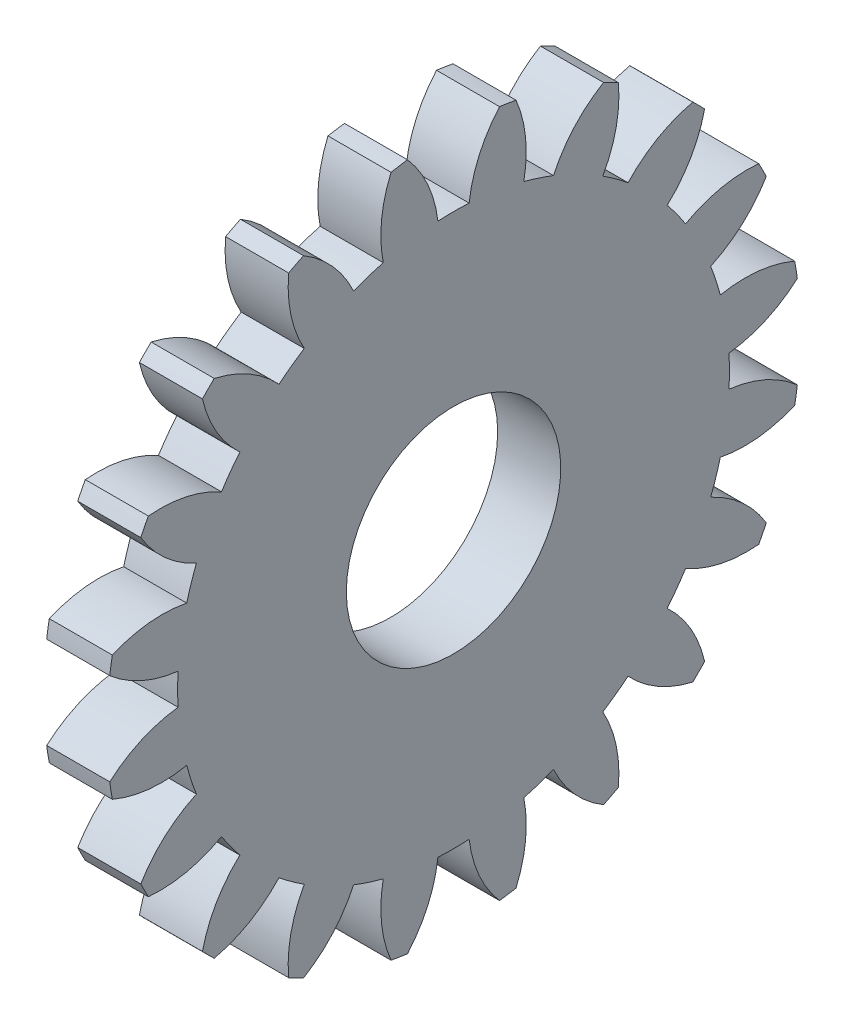
SolidWorks part; units mm, degrees
ref_plane "Plane1" through (0, 0, 0) normal (0, 0, 1) x (1, 0, 0)
ref_plane "Plane2" through (0, 0, 0) normal (0, 1, 0) x (1, 0, 0)
ref_plane "Plane3" through (0, 0, 0) normal (1, 0, 0) x (0, 0, -1)
sketch "HoldingSke" plane through (0, 0, 0) normal (0, 1, 0) x (1, 0, 0)
  line L0 (0, 0) -> (0.3759, -0.1368)
  line L1 (-15, 0) -> (100, 0) construction
  line L2 (0, 0) -> (-2.1039, 2.3779)
  line L3 (0, 0) -> (-11.863, 4.5341)
  line L4 (0, 0) -> (8.1152, 2.9537)
  line L5 (0, 0) -> (-46.8476, -17.4728)
  line L6 (0, 0) -> (-4.1448, -2.7965)
  line L7 (-2.1039, 2.3779) -> (8.6586, 51.2059)
  line L8 (-76.2, 54.61) -> (-73.4, 54.61)
  line L9 (-71.009, 38.7566) -> (-53.1078, 45.2721)
  line L10 (-76.2, 71.12) -> (104.1128, 71.12)
  line L11 (0, 0) -> (-5, 0)
  line L12 (-76.2, 101.6) -> (-76.113, 101.6)
  line L13 (24.9733, 27.94) -> (52.9518, 28.4284)
  line L14 (24.9733, 27.94) -> (24.9743, 27.94)
  line L15 (24.9733, 27.94) -> (100.4006, 29.5858)
  line L16 (-63.627, -2.5) -> (-12.827, -2.5)
  circle A0 centre (0, 0) radius 8.5
  circle A1 centre (0, 0) radius 21.874
  circle A2 centre (0, 0) radius 37.5
  circle A3 centre (0, 0) radius 8.5
  dimension "MHD" = 43.748
  dimension "Hub_dia" = 75
  dimension "Bore" = 17
  dimension "MBD" = 17
  dimension "Num_teeth" = 20
  dimension "Pitch" = 0.4
  dimension "Overall_len" = 50
  dimension "Show_teeth" = 20
  dimension "Thickness" = 5
  dimension "OAL" = 50.0001
  dimension "T_dim" = 2.8
  dimension "Ap" = 20
  dimension "H" = 19.05
  dimension "Pitch_radius" = 180.3128
  dimension "Width" = 5
  dimension "Backlash" = 0.087
  dimension "Addendum_fac" = 1
  dimension "Dedendum_fac" = 1.25
  dimension "Clearance_fac" = 0.25
  dimension "Dedendum_add" = 0.001
  dimension "Module" = 2.5
sketch "BasProSke" plane through (0, 0, 0) normal (0, 1, 0) x (1, 0, 0)
  line L0 (-10, 0) -> (60, 0) construction
  line L1 (0, 0) -> (0, 27.5)
  line L2 (0, 0) -> (5, 0)
  line L3 (5, 0) -> (5, 27.5)
  line L4 (5, 27.5) -> (0, 27.5)
  dimension "Thickness" = 5
  dimension "Diameter" = 55
revolve "Base-Revolve" add sketch "BasProSke" angle 360 about L0
sketch "TooCutSke" plane through (0, 0, 0) normal (1, 0, 0) x (0, 0, -1)
  line L1 (0, 0) -> (0, 107) construction
  line L2 (0, 0) -> (-2.1137, 24.9105) construction
  line L3 (0, 0) -> (-7.8012, 49.2549) construction
  line L4 (-2.1137, 24.9105) -> (-3.9006, 24.6275) construction
  arc A0 (1.2377, 21.839) -> (-1.2377, 21.839) centre (0, 0) ccw
  arc A1 (3.6672, 27.28) -> (-3.6672, 27.28) centre (0, 0) ccw
  circle A2 centre (0, 0) radius 25 construction
  circle A3 centre (0, 0) radius 23.4923 construction
  arc A4 (-1.2377, 21.839) -> (-3.6672, 27.28) centre (-11.1689, 20.6675) ccw
  arc A5 (3.6672, 27.28) -> (1.2377, 21.839) centre (11.1689, 20.6675) ccw
  dimension "Root_dia" = 43.748
  dimension "Overcut_dia" = 55.0508
  dimension "Pitch_dia" = 50
  dimension "Base_dia" = 46.9846
  dimension "Flank_rad" = 10
  dimension "Half_ang" = 9
  dimension "Half_CT" = 1.8092
extrude "ToothCut" cut sketch "TooCutSke" along normal through all
fillet "Breaks" [suppressed] radius 0.05
fillet "RootFillets" [suppressed] radius 0.626
pattern_circular "TeethCuts" count 20 every 18 about axis through (-10, 0, 0) along (1, 0, 0) of "ToothCut", "RootFillets", "Breaks"
sketch "HubNeaOneSke" plane through (0, 0, 0) normal (-1, 0, 0) x (0, 0, 1)
  circle A0 centre (0, 0) radius 21.874
  dimension "Diameter" = 43.748
extrude "HubNearOne" [suppressed] add sketch "HubNeaOneSke" along normal blind 45.0001
sketch "HubNeaBotSke" plane through (0, 0, 0) normal (-1, 0, 0) x (0, 0, 1)
  circle A0 centre (0, 0) radius 21.874
  dimension "Diameter" = 43.748
extrude "HubNearBoth" [suppressed] add sketch "HubNeaBotSke" along normal blind 22.5
ref_plane "FarPln" through (5, 0, 0) normal (1, 0, 0) x (0, 0, -1)
sketch "HubFarSke" plane through (5, 0, 0) normal (1, 0, 0) x (0, 0, -1)
  circle A0 centre (0, 0) radius 21.874
  dimension "Diameter" = 43.748
extrude "HubFar" [suppressed] add sketch "HubFarSke" along normal blind 22.5
sketch "BorSke" plane through (0, 0, 0) normal (1, 0, 0) x (0, 0, -1)
  circle A0 centre (0, 0) radius 8.5
  dimension "Diameter" = 17
extrude "Bore" cut sketch "BorSke" along normal mid plane 100.0001
sketch "KeySke" plane through (0, 0, 0) normal (1, 0, 0) x (0, 0, -1)
  line L0 (-3, 0) -> (-3, 11.3)
  line L1 (-3, 11.3) -> (3, 11.3)
  line L2 (3, 11.3) -> (3, 0)
  line L3 (0, 0) -> (0, 34) construction
  line L4 (-3, 0) -> (3, 0)
  dimension "Offset" = 11.3
  dimension "Width" = 6
extrude "Keyway" [suppressed] cut sketch "KeySke" along normal mid plane 100.0001
pattern_circular "Keyway2" [suppressed] count 2 every 90 about axis through (-10, 0, 0) along (1, 0, 0)
equation "' \"Module@HoldingSke\" = 6.35"
equation "' \"Num_teeth@HoldingSke\" = 12"
equation "' \"Ap@HoldingSke\" =  20"
equation "' \"Ap@HoldingSke\" = 20"
equation "' \"Width@HoldingSke\" = 0.5 * 25.4"
equation "' \"Hub_dia@HoldingSke\"= 1 * 25.4"
equation "' \"Hub_dia@HoldingSke\" = 1 * 25.4"
equation "' \"Overall_len@HoldingSke\" = 1.0 * 25.4"
equation "' \"Bore@HoldingSke\" = 0.75 * 25.4"
equation "' \"T_dim@HoldingSke\" = 0.1 * 25.4"
equation "' \"Width@KeySke\" = 0.25 * 25.4"
equation "' \"Show_teeth@HoldingSke\" = 13"
equation "' \"Backlash@HoldingSke\" = 0.009 * 25.4"
equation "' \"Addendum_fac@HoldingSke\" = 1.0"
equation "' \"Dedendum_fac@HoldingSke\" = 1.25"
equation "' \"Dedendum_add@HoldingSke\" = 0.00005 * 25.4"
equation "' \"Clearance_fac@HoldingSke\" = 0.25"
equation "\"Pitch@HoldingSke\" = 1 / \"Module@HoldingSke\""
equation "\"Overcut_dia@TooCutSke\" = (\"Num_teeth@HoldingSke\" + 2 * \"Addendum_fac@HoldingSke\") / \"Pitch@HoldingSke\" + 0.002 * 25.4"
equation "\"Pitch_dia@TooCutSke\" = \"Num_teeth@HoldingSke\" / \"Pitch@HoldingSke\""
equation "\"Base_dia@TooCutSke\" = \"Num_teeth@HoldingSke\" / \"Pitch@HoldingSke\" * cos((\"Ap@HoldingSke\"  * 3.14159265 / 180))"
equation "\"Root_dia@TooCutSke\" = (\"Num_teeth@HoldingSke\" + 2) / \"Pitch@HoldingSke\" - 2 * (\"Addendum_fac@HoldingSke\" + \"Dedendum_fac@HoldingSke\") / \"Pitch@HoldingSke\" - \"Dedendum_add@HoldingSke\" * 2"
equation "\"Half_ang@TooCutSke\" = 180 / \"Num_teeth@HoldingSke\""
equation "\"Half_CT@TooCutSke\" = \"Num_teeth@HoldingSke\" / \"Pitch@HoldingSke\" * sin((3.14159265 / 2 / \"Num_teeth@HoldingSke\")) / 2 - 7 * \"Backlash@HoldingSke\" / 4"
equation "\"Flank_rad@TooCutSke\" = \"Num_teeth@HoldingSke\" / \"Pitch@HoldingSke\" / 5"
equation "\"Radius@RootFillets\" = \"Clearance_fac@HoldingSke\" / \"Pitch@HoldingSke\" + \"Dedendum_add@HoldingSke\""
equation "\"Break_rad@Breaks\" = 0.02 / \"Pitch@HoldingSke\""
equation "\"Thickness@HoldingSke\" = \"Width@HoldingSke\""
equation "\"OAL@HoldingSke\" = \"Thickness@HoldingSke\""
equation "\"MHD@HoldingSke\" = (\"Num_teeth@HoldingSke\" + 2) / \"Pitch@HoldingSke\" - 2 * (\"Addendum_fac@HoldingSke\" + \"Dedendum_fac@HoldingSke\")  / \"Pitch@HoldingSke\" - \"Dedendum_add@HoldingSke\" * 2"
equation "\"MBD@HoldingSke\" = (\"Num_teeth@HoldingSke\" + 2) / \"Pitch@HoldingSke\" - 2 * (\"Addendum_fac@HoldingSke\" + \"Dedendum_fac@HoldingSke\")  / \"Pitch@HoldingSke\" - \"Dedendum_add@HoldingSke\" * 2 - 0.002 * 25.4"
equation "\"MHD@HoldingSke\" = ((sgn( \"MHD@HoldingSke\" - \"Hub_dia@HoldingSke\" )-1)*( \"MHD@HoldingSke\" - \"Hub_dia@HoldingSke\" ))/-2+ \"Hub_dia@HoldingSke\""
equation "\"MBD@HoldingSke\" = ((sgn( \"MBD@HoldingSke\" - \"Bore@HoldingSke\" )-1)*( \"MBD@HoldingSke\" - \"Bore@HoldingSke\" ))/-2+ \"Bore@HoldingSke\""
equation "\"OAL@HoldingSke\" = ((sgn( \"OAL@HoldingSke\" - \"Overall_len@HoldingSke\" )+1)*( \"OAL@HoldingSke\" - \"Overall_len@HoldingSke\" ))/2 + \"Overall_len@HoldingSke\" + 0.000002 * 25.4"
equation "\"Num_teeth@TeethCuts\" = int( \"Show_teeth@HoldingSke\" ) + 1"
equation "\"Num_teeth@TeethCuts\" = ((sgn( \"Num_teeth@TeethCuts\" - \"Num_teeth@HoldingSke\" )-1)*( \"Num_teeth@TeethCuts\" - \"Num_teeth@HoldingSke\" ))/-2+ \"Num_teeth@HoldingSke\""
equation "\"Num_teeth@TeethCuts\" = ((sgn( \"Num_teeth@TeethCuts\" - 2.0)+1)*( \"Num_teeth@TeethCuts\" - 2.0))/2 +2.0"
equation "\"Angle@TeethCuts\" = 360.0 / \"Num_teeth@HoldingSke\""
equation "\"Diameter@BasProSke\" = (\"Num_teeth@HoldingSke\" + 2 * \"Addendum_fac@HoldingSke\") / \"Pitch@HoldingSke\""
equation "\"Thickness@BasProSke\"  = \"Thickness@HoldingSke\""
equation "' \"Fillet_rad@BasProSke\" =  \"Thickness@HoldingSke\" * 0.05"
equation "' \"Fillet_rad@BasProSke\" = \"Thickness@HoldingSke\" * 0.05"
equation "\"MHD@HoldingSke\" = ((sgn( \"MHD@HoldingSke\" - \"Root_dia@TooCutSke\" )-1)*( \"MHD@HoldingSke\" - \"Root_dia@TooCutSke\" ))/-2+ \"Root_dia@TooCutSke\""
equation "\"Diameter@HubNeaOneSke\" = \"MHD@HoldingSke\""
equation "\"Length@HubNearOne\" = \"OAL@HoldingSke\" - \"Thickness@BasProSke\""
equation "\"Diameter@HubNeaBotSke\" = \"MHD@HoldingSke\""
equation "\"Length@HubNearBoth\" = ( \"OAL@HoldingSke\" - \"Thickness@BasProSke\" ) / 2.0"
equation "\"Thickness@FarPln\" = \"Thickness@BasProSke\""
equation "\"Diameter@HubFarSke\" = \"MHD@HoldingSke\""
equation "\"Length@HubFar\" = ( \"OAL@HoldingSke\" - \"Thickness@BasProSke\" ) / 2.0"
equation "\"Diameter@BorSke\" = \"MBD@HoldingSke\""
equation "\"D1@Bore\" = \"OAL@HoldingSke\" * 2.0"
equation "\"D1@Keyway\" = \"OAL@HoldingSke\" * 2.0"
equation "\"Offset@KeySke\" = \"T_dim@HoldingSke\" + \"MBD@HoldingSke\" / 2.0"
